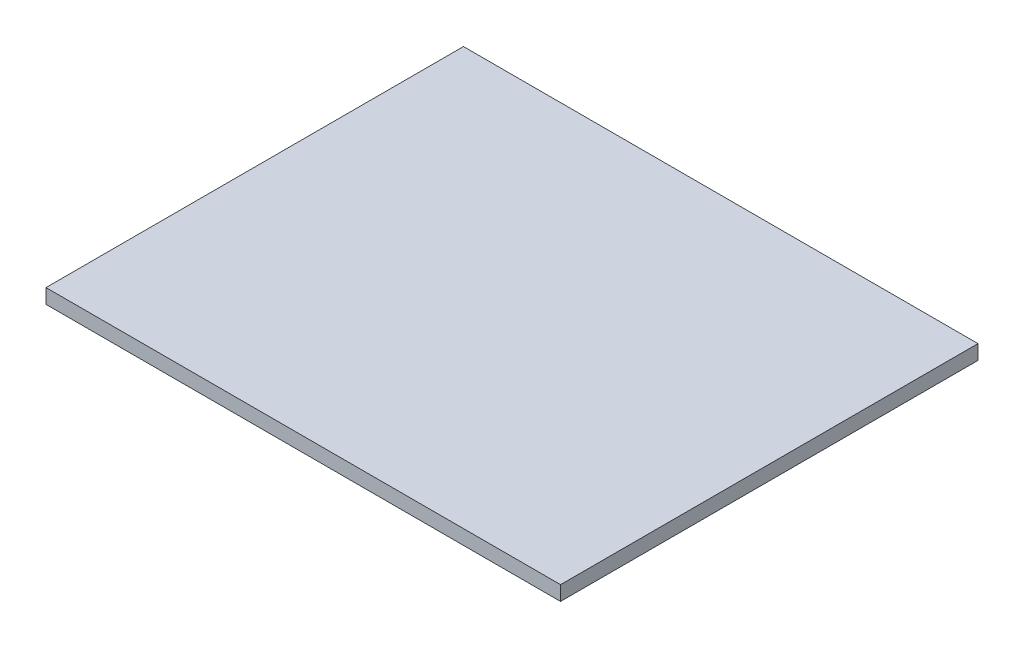
SolidWorks part; units mm, degrees
ref_plane "Front Plane" through (0, 0, 0) normal (0, 0, 1) x (1, 0, 0)
ref_plane "Top Plane" through (0, 0, 0) normal (0, 1, 0) x (1, 0, 0)
ref_plane "Right Plane" through (0, 0, 0) normal (1, 0, 0) x (0, 0, -1)
sketch "Sketch1" plane through (0, 0, 0) normal (0, 1, 0) x (1, 0, 0)
  line L1 (-29.4787, 11.5039) -> (23.5213, 11.5039)
  line L2 (-29.4787, 11.5039) -> (-29.4787, -31.4961)
  line L3 (-29.4787, -31.4961) -> (23.5213, -31.4961)
  line L4 (23.5213, 11.5039) -> (23.5213, -31.4961)
  dimension "D1" = 53
  dimension "D2" = 43
extrude "Boss-Extrude1" add sketch "Sketch1" along normal blind 1.5
